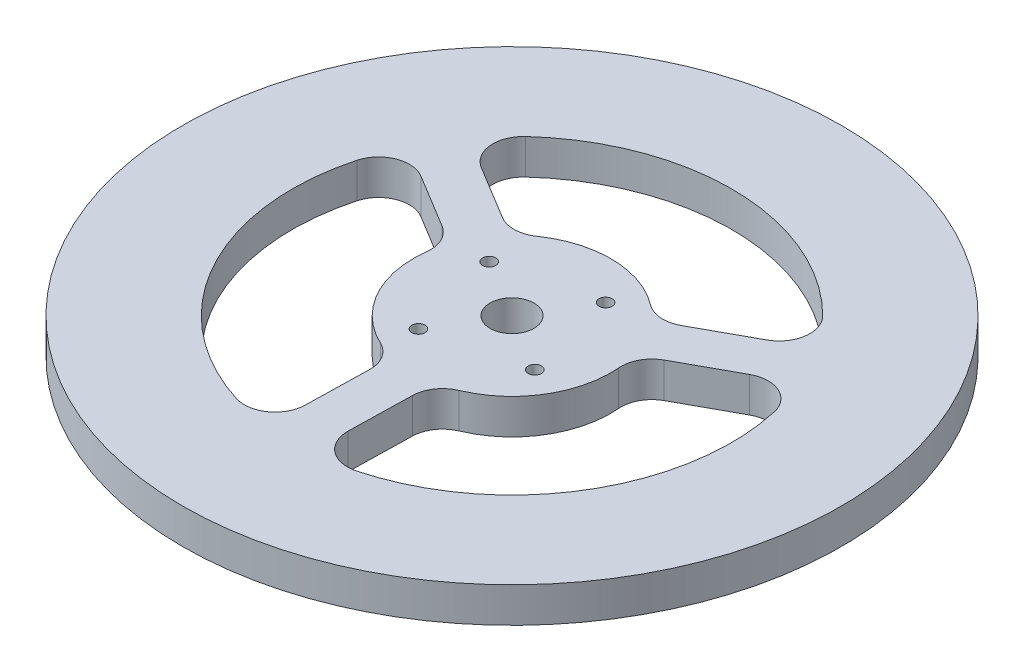
SolidWorks part; units mm, degrees
ref_plane "前视基准面" through (0, 0, 0) normal (0, 0, 1) x (1, 0, 0)
ref_plane "上视基准面" through (0, 0, 0) normal (0, 1, 0) x (1, 0, 0)
ref_plane "右视基准面" through (0, 0, 0) normal (1, 0, 0) x (0, 0, -1)
other "Configuration Table"
sketch "草图1" plane through (0, 0, 0) normal (0, 1, 0) x (1, 0, 0)
  line L1 (-42.7377, 25.9517) -> (-81.9251, 49.7476) construction
  line L2 (-0.4977, -22.4945) -> (-1.106, -49.9878) construction
  line L3 (-5.484, -21.8214) -> (-6.0992, -49.6266)
  line L4 (-45.1186, 21.5479) -> (-21.3462, 7.1125)
  line L5 (-39.9283, 30.0954) -> (-16.1559, 15.66)
  line L6 (4.5135, -22.0426) -> (3.8983, -49.8478)
  line L7 (16.8327, 14.9301) -> (41.2203, 28.2999)
  line L8 (65.7655, 36.0541) -> (77.2233, 42.3355) construction
  line L11 (21.6399, 6.1614) -> (46.0275, 19.5312)
  circle A0 centre (0, 0) radius 75
  arc A1 (-21.3462, 7.1125) -> (-5.484, -21.8214) centre (0, 0) ccw
  arc A2 (-45.1186, 21.5479) -> (-6.0992, -49.6266) centre (0, 0) ccw
  arc A3 (41.2203, 28.2999) -> (-39.9283, 30.0954) centre (0, 0) ccw
  arc A4 (3.8983, -49.8478) -> (46.0275, 19.5312) centre (0, 0) ccw
  arc A5 (16.8327, 14.9301) -> (-16.1559, 15.66) centre (0, 0) ccw
  arc A6 (4.5135, -22.0426) -> (21.6399, 6.1614) centre (0, 0) ccw
  dimension "D1" = 150
  dimension "D3" = 120
  dimension "D5" = 5
extrude "凸台-拉伸1" add sketch "草图1" along normal blind 8
fillet "圆角1" radius 7 1 edges at (41.2203, 4, -28.2999)
fillet "圆角2" radius 7 1 edges at (-39.9283, 4, -30.0954)
fillet "圆角3" radius 7 4 edges at (3.8983, 4, 49.8478) (46.0275, 4, -19.5312) (-45.1186, 4, -21.5479) (-6.0992, 4, 49.6266)
sketch "草图2" plane through (0, 8, 0) normal (0, 1, 0) x (1, 0, 0)
  circle A0 centre (0, 0) radius 5
extrude "切除-拉伸1" cut sketch "草图2" against normal blind 10
sketch "草图3" plane through (0, 8, 0) normal (0, 1, 0) x (1, 0, 0)
  line L0 (0, 0) -> (-64.1065, 38.9276) construction
  line L1 (-21.3462, 7.1125) -> (-37.8893, 17.158) construction
  circle A0 centre (-13.2487, 8.045) radius 1.5
  circle A4 centre (0, 0) radius 75 construction
  circle A5 centre (8.045, 13.2487) radius 1.5
  circle A6 centre (13.2487, -8.045) radius 1.5
  circle A7 centre (-8.045, -13.2487) radius 1.5
  point P19 (0, 0)
  dimension "D1" = 15.5
  dimension "D2" = 0
  dimension "D3" = 4
extrude "切除-拉伸2" cut sketch "草图3" against normal blind 10
fillet "圆角4" radius 7 6 edges at (-21.3462, 4, -7.1125) (-5.484, 4, 21.8214) (-16.1559, 4, -15.66) (16.8327, 4, -14.9301) (21.6399, 4, -6.1614) (4.5135, 4, 22.0426)
